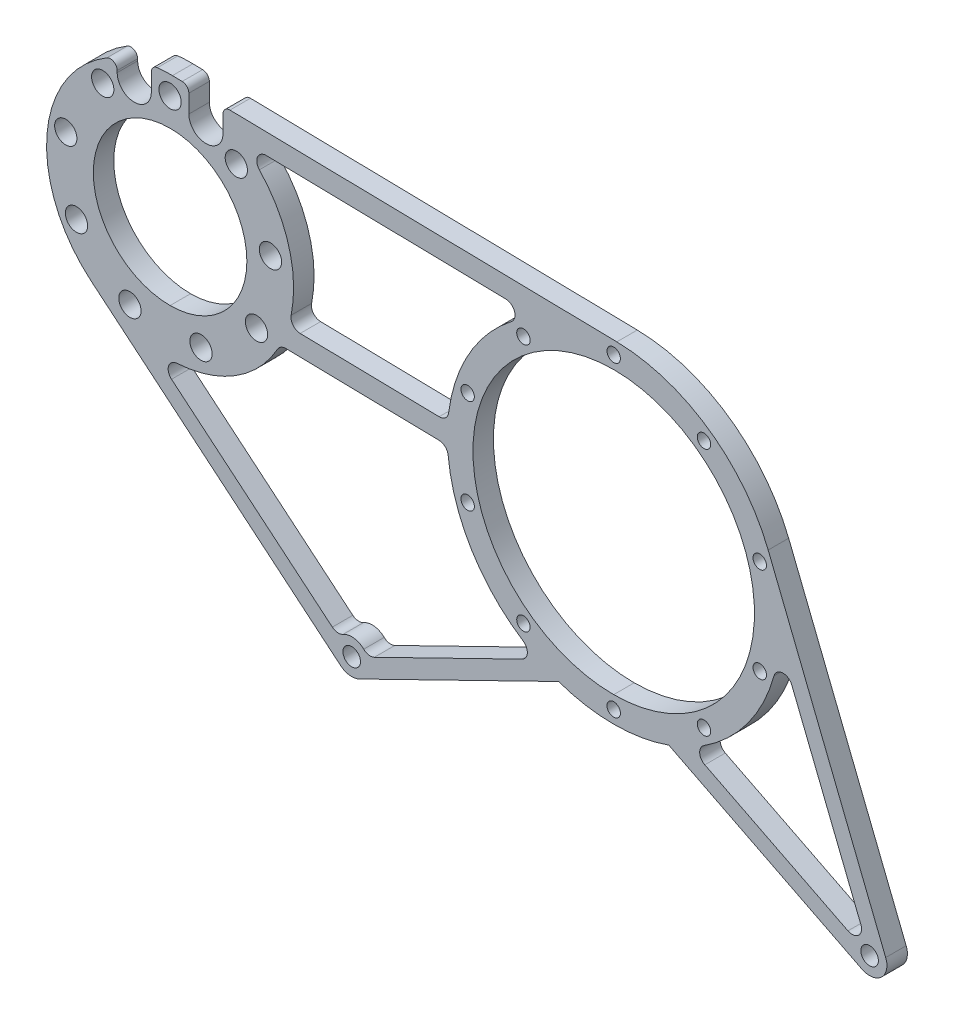
SolidWorks part; units mm, degrees
material "6061-T6 (SS)"
ref_plane "Front Plane" through (0, 0, 0) normal (0, 0, 1) x (1, 0, 0)
ref_plane "Top Plane" through (0, 0, 0) normal (0, 1, 0) x (1, 0, 0)
ref_plane "Right Plane" through (0, 0, 0) normal (1, 0, 0) x (0, 0, -1)
sketch "Sketch2" plane through (0, 0, 0) normal (0, 0, 1) x (1, 0, 0)
  line L0 (-114.3, 107.95) -> (-114.3, 95.25) construction
  line L1 (-308.8661, 91.7104) -> (-215.9264, 14.1075)
  line L2 (-278.5345, 172.9659) -> (-274.9034, 172.8975)
  line L3 (-13.0706, 21.4387) -> (-56.8054, 130.918)
  line L4 (-208.9705, 13.2659) -> (-134.815, 49.5352)
  line L5 (-21.9498, 13.301) -> (-93.785, 49.5352)
  line L6 (-259.7112, 163.648) -> (-259.7112, 170.0232)
  line L7 (-272.4112, 163.648) -> (-272.4112, 170.3579)
  line L8 (-257.1234, 172.5627) -> (-113.1345, 169.8515)
  line L9 (-286.3888, 163.648) -> (-286.3888, 170.2056)
  line L10 (-299.0888, 163.648) -> (-299.0888, 164.3148)
  circle A0 centre (-279.4, 127) radius 28.575
  circle A1 centre (-114.3, 95.25) radius 36 construction
  circle A2 centre (0, 0) radius 12.7 construction
  circle A3 centre (-228.6, 0) radius 12.7 construction
  arc A4 (-278.5345, 172.9659) -> (-284.1089, 172.7322) centre (-279.4, 127) ccw
  arc A5 (-134.815, 49.5352) -> (-93.785, 49.5352) centre (-114.3, 107.95) ccw
  circle A6 centre (-19.05, 19.05) radius 3.2639
  circle A7 centre (-211.7995, 19.05) radius 3.2639
  arc A8 (-215.9264, 14.1075) -> (-208.9705, 13.2659) centre (-211.7995, 19.05) ccw
  arc A9 (-21.9498, 13.301) -> (-13.0706, 21.4387) centre (-19.05, 19.05) ccw
  circle A10 centre (-114.3, 107.95) radius 52.3875
  arc A11 (-56.8054, 130.918) -> (-113.1345, 169.8515) centre (-114.3, 107.95) ccw
  arc A12 (-307.0309, 90.178) -> (-276.144, 172.9208) centre (-279.4, 127) ccw construction
  arc A13 (-272.4112, 163.648) -> (-259.7112, 163.648) centre (-266.0612, 163.648) ccw
  arc A14 (-257.1234, 172.5627) -> (-259.7112, 170.0232) centre (-257.1712, 170.0232) ccw
  arc A15 (-274.9034, 172.8975) -> (-272.4112, 170.3579) centre (-274.9512, 170.3579) cw
  arc A16 (-299.0888, 163.648) -> (-286.3888, 163.648) centre (-292.7388, 163.648) ccw
  arc A17 (-302.9287, 166.4969) -> (-308.8661, 91.7104) centre (-279.4, 127) ccw
  arc A18 (-302.9287, 166.4969) -> (-299.0888, 164.3148) centre (-301.6288, 164.3148) cw
  arc A19 (-284.1089, 172.7322) -> (-286.3888, 170.2056) centre (-283.8488, 170.2056) ccw
  point P10 (-279.4, 166)
  point P18 (-266.0612, 163.648)
  point P26 (-292.7388, 163.648)
  point P36 (-259.7112, 172.6114)
  point P47 (-299.0888, 168.5447)
  point P51 (-279.4, 127)
  point P52 (-114.3, 95.25)
  point P53 (-279.4, 127)
  point P54 (-114.3, 95.25)
  dimension "D1" = 25.4
  dimension "D2" = 25.4
  dimension "D8" = 57.15
  dimension "D9" = 72
  dimension "D10" = 91.948
  dimension "D12" = 123.825
  dimension "D13" = 6.5278
  dimension "D16" = 6.5278
  dimension "D18" = 3.175
  dimension "D20" = 104.775
  dimension "D25" = 2.54
  dimension "D26" = 2.54
  dimension "D27" = 2.54
  dimension "D28" = 46.0361
  dimension "D29" = 6.35
  dimension "D30" = 6.35
  dimension "D31" = 6.5576
  dimension "D3" = 228.6
  dimension "D4" = 114.3
  dimension "D5" = 95.25
  dimension "D6" = 279.4
  dimension "D7" = 127
  dimension "D11" = 12.7
  dimension "D14" = 19.05
  dimension "D15" = 19.05
  dimension "D17" = 25.4
  dimension "D19" = 82.55
  dimension "D21" = 39
  dimension "D22" = 13.3388
  dimension "D23" = 2.352
  dimension "D24" = 13.3388
  dimension "D32" = 6.7099
  dimension "D33" = 6.3751
extrude "Boss-Extrude1" add sketch "Sketch2" along normal blind 7.62
sketch "Sketch3" plane through (0, 0, 7.62) normal (0, 0, 1) x (1, 0, 0)
  line L0 (-279.4, 127) -> (-279.4, 166.0004) construction
  line L1 (-114.3, 107.95) -> (-114.3, 165.1) construction
  circle A0 centre (-279.4, 127) radius 39.0004 construction
  circle A1 centre (-279.4, 166.0004) radius 4.15
  circle A2 centre (-254.7465, 156.3809) radius 4.15
  circle A3 centre (-242.0442, 133.1649) radius 4.15
  circle A4 centre (-247.2366, 107.2156) radius 4.15
  circle A5 centre (-267.8941, 90.6748) radius 4.15
  circle A6 centre (-294.3509, 91.2822) radius 4.15
  circle A7 centre (-314.2275, 108.7537) radius 4.15
  circle A8 centre (-318.2234, 134.914) radius 4.15
  circle A9 centre (-304.469, 157.5225) radius 4.15
  circle A10 centre (-114.3, 107.95) radius 57.15 construction
  circle A11 centre (-114.3, 165.1) radius 2.5
  circle A12 centre (-80.7081, 154.1853) radius 2.5
  circle A13 centre (-59.9471, 125.6103) radius 2.5
  circle A14 centre (-59.9471, 90.2897) radius 2.5
  circle A15 centre (-80.7081, 61.7147) radius 2.5
  circle A16 centre (-114.3, 50.8) radius 2.5
  circle A17 centre (-147.8919, 61.7147) radius 2.5
  circle A18 centre (-168.6529, 90.2897) radius 2.5
  circle A19 centre (-168.6529, 125.6103) radius 2.5
  circle A20 centre (-147.8919, 154.1853) radius 2.5
  point P24 (-280.288, 127.3232)
  point P48 (-114.3, 107.95)
  dimension "D1" = 78.0009
  dimension "D2" = 8.3
  dimension "D4" = 114.3
  dimension "D5" = 5
  dimension "D3" = 9
  dimension "D6" = 10
extrude "Cut-Extrude1" cut sketch "Sketch3" against normal through all both and the other way through all
sketch "Sketch4" plane through (0, 0, 7.62) normal (0, 0, 1) x (1, 0, 0)
  line L0 (-278.8626, 74.9306) -> (-219.0181, 24.9616)
  line L1 (-48.0193, 91.8071) -> (-22.3039, 27.4349)
  line L2 (-308.8661, 91.7104) -> (-215.9264, 14.1075) construction
  line L3 (-148.3931, 49.9629) -> (-203.3792, 23.0694)
  line L4 (-208.9705, 13.2659) -> (-134.815, 49.5352) construction
  line L5 (-243.5899, 164.6865) -> (-154.4674, 163.0084)
  line L6 (-274.9034, 172.8975) -> (-278.5345, 172.9659) construction
  line L7 (-80.3879, 49.8896) -> (-27.12, 23.021)
  line L8 (-93.785, 49.5352) -> (-21.9498, 13.301) construction
  line L9 (-13.0706, 21.4387) -> (-56.8054, 130.918) construction
  line L10 (-230.9935, 113.6403) -> (-179.2537, 112.6661)
  line L11 (-236.2891, 106.1187) -> (-179.3258, 105.0461)
  arc A0 (-234.35, 117.8289) -> (-239.394, 104.3477) centre (-279.4, 127) ccw construction
  arc A1 (-175.9158, 101.8958) -> (-175.723, 115.7197) centre (-114.3, 107.95) ccw construction
  circle A2 centre (-19.05, 19.05) radius 6.4389 construction
  circle A3 centre (-211.7995, 19.05) radius 6.4389 construction
  arc A4 (-278.5345, 172.9659) -> (-284.1089, 172.7322) centre (-279.4, 127) ccw construction
  arc A5 (-246.1793, 158.7804) -> (-234.35, 117.8289) centre (-279.4, 127) cw
  arc A6 (-152.3848, 156.763) -> (-175.723, 115.7197) centre (-114.3, 107.95) ccw
  arc A7 (-54.6287, 91.4427) -> (-80.7099, 55.9417) centre (-114.3, 107.95) cw
  arc A8 (-154.4674, 163.0084) -> (-152.3848, 156.763) centre (-154.5331, 159.5166) cw
  arc A9 (-243.5899, 164.6865) -> (-246.1793, 158.7804) centre (-243.6556, 161.1946) ccw
  arc A10 (-278.8626, 74.9306) -> (-276.8202, 81.0984) centre (-276.6242, 77.6114) cw
  arc A11 (-148.0251, 56.0292) -> (-148.3931, 49.9629) centre (-149.9276, 53.1003) cw
  arc A12 (-80.3879, 49.8896) -> (-80.7099, 55.9417) centre (-78.8151, 53.0079) cw
  arc A13 (-48.0193, 91.8071) -> (-54.6287, 91.4427) centre (-51.2626, 90.5115) ccw
  arc A14 (-27.12, 23.021) -> (-22.3039, 27.4349) centre (-25.5472, 26.1393) ccw
  arc A15 (-215.0283, 24.6208) -> (-207.3352, 23.69) centre (-211.7995, 19.05) cw
  arc A16 (-203.3792, 23.0694) -> (-207.3352, 23.69) centre (-204.9137, 26.2067) cw
  arc A17 (-219.0181, 24.9616) -> (-215.0283, 24.6208) centre (-216.7797, 27.6425) ccw
  arc A18 (-239.394, 104.3477) -> (-276.8202, 81.0984) centre (-279.4, 127) cw
  arc A19 (-175.9158, 101.8958) -> (-148.0251, 56.0292) centre (-114.3, 107.95) ccw
  arc A20 (-179.3258, 105.0461) -> (-175.9158, 101.8958) centre (-179.3915, 101.5543) cw
  arc A21 (-179.2537, 112.6661) -> (-175.723, 115.7197) centre (-179.1879, 116.158) ccw
  arc A22 (-230.9935, 113.6403) -> (-234.35, 117.8289) centre (-230.9277, 117.1322) cw
  arc A23 (-236.2891, 106.1187) -> (-239.394, 104.3477) centre (-236.3549, 102.6268) ccw
  point P40 (-253.3333, 164.87)
  point P43 (-286.9003, 81.6419)
  point P46 (-142.5125, 52.8391)
  point P50 (-52.5701, 103.1988)
  point P56 (-216.7985, 23.1083)
  dimension "D1" = 61.9125
  dimension "D2" = 12.8778
  dimension "D3" = 12.8778
  dimension "D9" = 3.4925
  dimension "D10" = 61.9125
  dimension "D11" = 3.4925
  dimension "D14" = 3.4925
  dimension "D4" = 6.35
  dimension "D5" = 6.35
  dimension "D6" = 7.62
  dimension "D7" = 6.35
  dimension "D8" = 6.35
  dimension "D12" = 50.8
  dimension "D13" = 7.62
extrude "Cut-Extrude2" cut sketch "Sketch4" against normal through all both and the other way through all
ref_plane "Plane3" through (0, 0, 3.81) normal (0, 0, 1) x (1, 0, 0)
ref_plane "Plane4" through (-114.3, 0, 0) normal (1, 0, 0) x (0, 0, -1)
ref_plane "Plane5" through (-279.4, 0, 0) normal (1, 0, 0) x (0, 0, -1)
split line "Split Line1"
split line "Split Line2"
sketch "Sketch5" plane through (0, 0, 7.62) normal (0, 0, 1) x (1, 0, 0)
  point P0 (-279.4, 127)
  point P1 (-114.3, 107.95)
